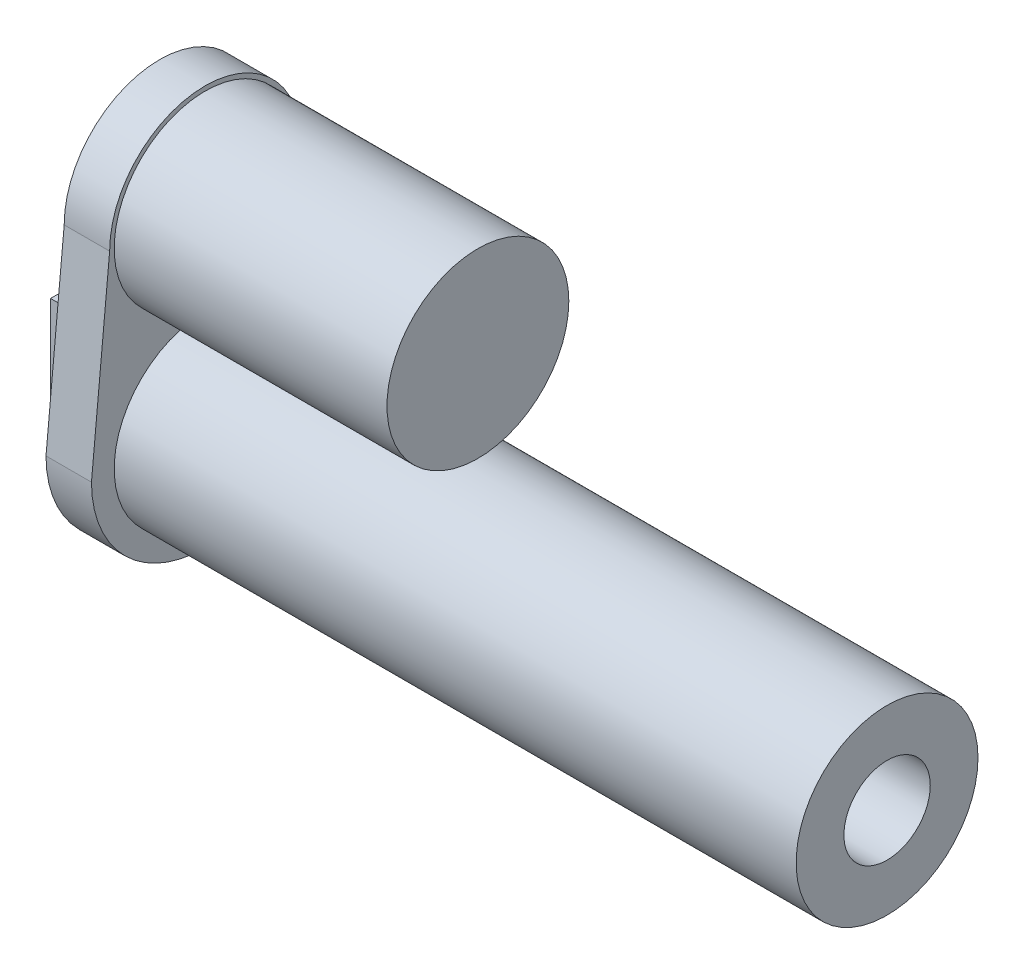
SolidWorks part; units mm, degrees
material "AISI 1020 Steel, Cold Rolled"
ref_plane "Front Plane" through (0, 0, 0) normal (0, 0, 1) x (1, 0, 0)
ref_plane "Top Plane" through (0, 0, 0) normal (0, 1, 0) x (1, 0, 0)
ref_plane "Right Plane" through (0, 0, 0) normal (1, 0, 0) x (0, 0, -1)
sketch "Sketch1" plane through (0, 0, 0) normal (1, 0, 0) x (0, 0, -1)
  line L0 (-21, 42) -> (-25, 0)
  line L3 (21, 42) -> (25, 0)
  arc A0 (21, 42) -> (-21, 42) centre (0, 42) ccw
  arc A1 (25, 0) -> (-25, 0) centre (0, 0) cw
extrude "Boss-Extrude1" add sketch "Sketch1" along normal blind 10
sketch "Sketch2" plane through (0, 0, 0) normal (-1, 0, 0) x (0, 0, 1)
  line L2 (0, 9.5) -> (-4, 9.5)
  line L3 (-4, 9.5) -> (-4, -9.5)
  line L4 (-4, -9.5) -> (4, -9.5)
  line L5 (4, -9.5) -> (4, 9.5)
  line L6 (4, 9.5) -> (0, 9.5)
extrude "Boss-Extrude2" add sketch "Sketch2" along normal blind 20
sketch "Sketch3" plane through (0, 0, -4) normal (0, 0, -1) x (-1, 0, 0)
  line L0 (20, 0) -> (11, 0)
  line L1 (20, 9.5) -> (20, -9.5) construction
  circle A0 centre (11, 0) radius 4.5
extrude "Cut-Extrude1" cut sketch "Sketch3" against normal through all
sketch "Sketch5" plane through (10, 0, 0) normal (1, 0, 0) x (0, 0, -1)
  circle A0 centre (0, 0) radius 20
extrude "Boss-Extrude4" add sketch "Sketch5" along normal blind 150
sketch "Sketch6" plane through (10, 0, 0) normal (1, 0, 0) x (0, 0, -1)
  line L0 (21, 42) -> (-21, 42)
  circle A0 centre (0, 42) radius 20
extrude "Boss-Extrude5" add sketch "Sketch6" along normal blind 60 contours L0 A0 | L0 A0
sketch "Sketch7" plane through (160, 0, 0) normal (1, 0, 0) x (0, 0, -1)
  circle A0 centre (0, 0) radius 9.5
extrude "Cut-Extrude2" cut sketch "Sketch7" against normal blind 150
